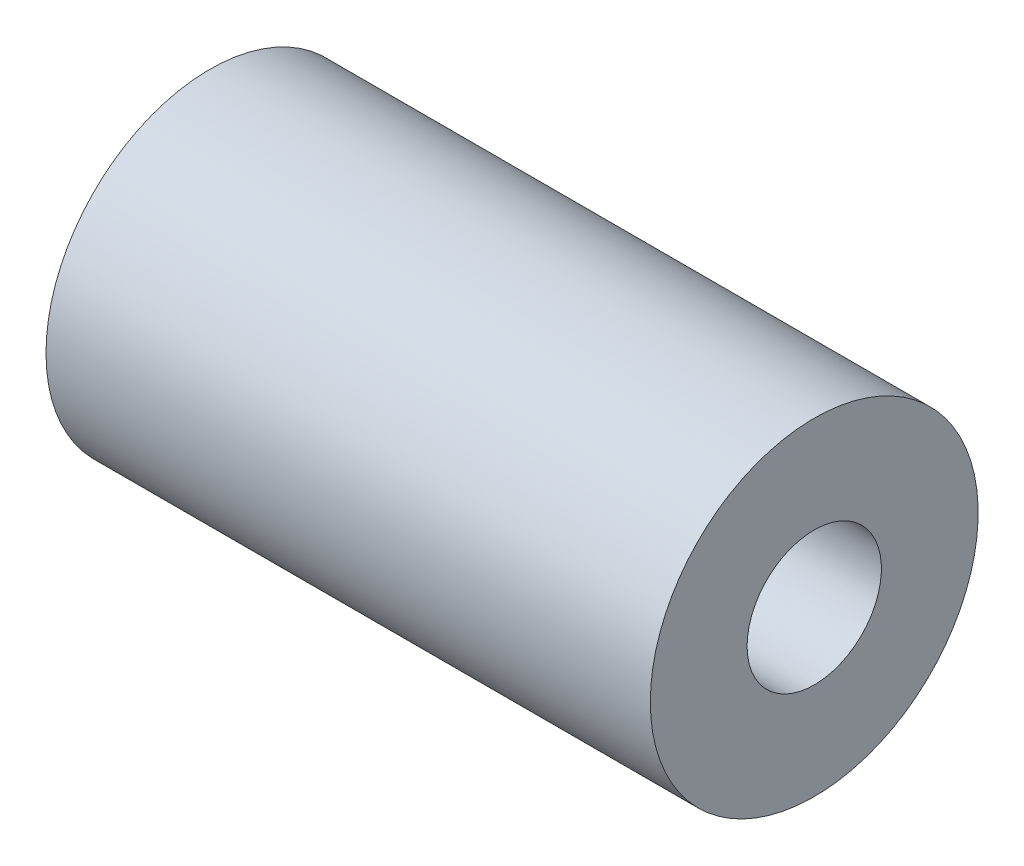
SolidWorks part; units mm, degrees
ref_plane "Front Plane" through (0, 0, 0) normal (0, 0, 1) x (1, 0, 0)
ref_plane "Top Plane" through (0, 0, 0) normal (0, 1, 0) x (1, 0, 0)
ref_plane "Right Plane" through (0, 0, 0) normal (1, 0, 0) x (0, 0, -1)
sketch "Sketch1" plane through (0, 0, 0) normal (0, 0, 1) x (1, 0, 0)
  line L1 (0, 0) -> (55.9195, 0) construction
  line L3 (0, -6.35) -> (57.15, -6.35)
  line L4 (0, -6.35) -> (0, -15.5)
  line L5 (0, -15.5) -> (57.15, -15.5)
  line L6 (57.15, -6.35) -> (57.15, -15.5)
  point P0 (0, 0)
  point P8 (0, 0)
  dimension "D1" = 57.15
  dimension "D2" = 6.35
  dimension "D3" = 15.5
revolve "Revolve1" add sketch "Sketch1" angle 360 about L1
